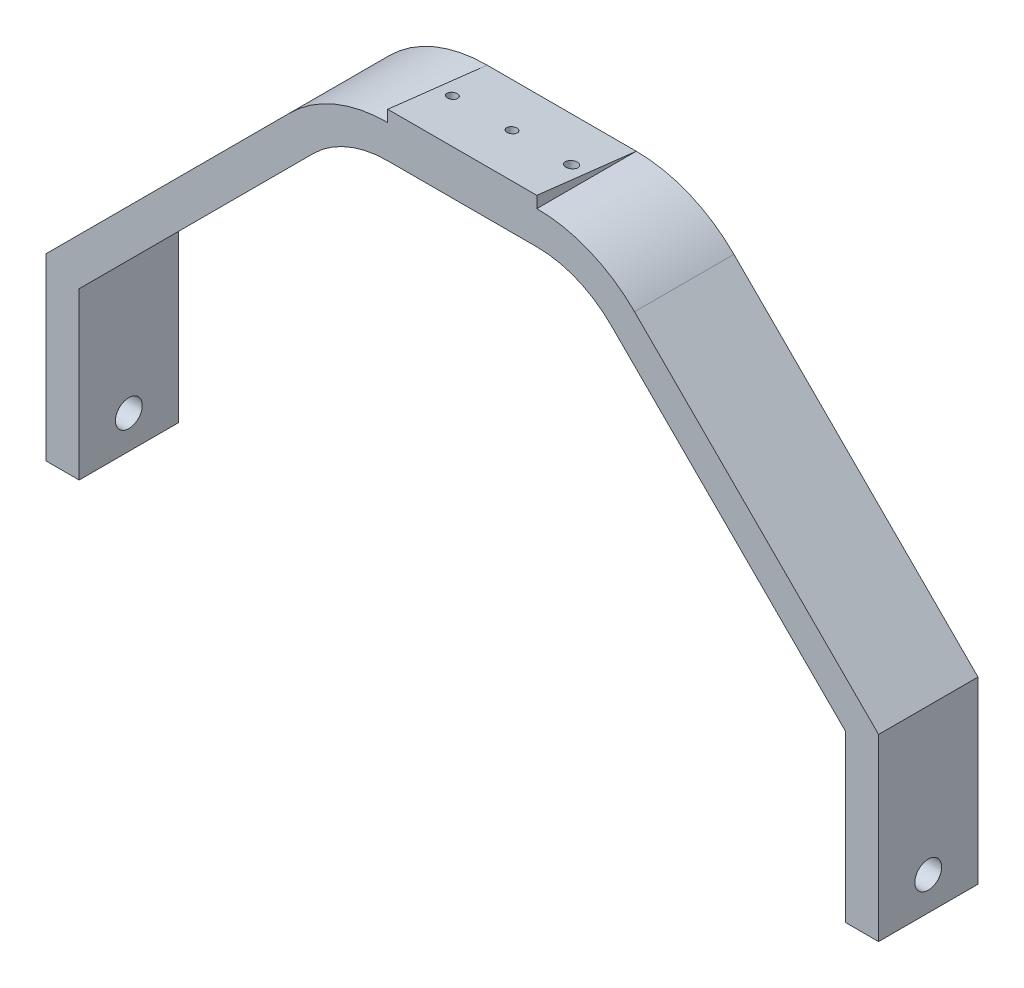
SolidWorks part; units mm, degrees
ref_plane "Alzado" through (0, 0, 0) normal (0, 0, 1) x (1, 0, 0)
ref_plane "Planta" through (0, 0, 0) normal (0, 1, 0) x (1, 0, 0)
ref_plane "Vista lateral" through (0, 0, 0) normal (1, 0, 0) x (0, 0, -1)
sketch "Croquis1" plane through (0, 0, 0) normal (0, 0, 1) x (1, 0, 0)
  line L0 (-22.5, -36.6894) -> (-68.1161, -36.6894) construction
  line L1 (-22.5, -5) -> (22.5, -5)
  line L3 (-22.5, 5) -> (22.5, 5)
  line L5 (0, -5) -> (0, 9.8205) construction
  line L6 (-51.9789, -7.2106) -> (-122.6896, -77.9212)
  line L7 (-68.1161, -36.6894) -> (22.5, -36.6894) construction
  line L8 (-22.5, -36.6894) -> (-55.2569, -3.9326) construction
  line L9 (-44.9078, -14.2816) -> (-115.6185, -84.9923)
  line L12 (-115.6185, -84.9923) -> (-115.6185, -134.9923)
  line L14 (22.5, -36.6894) -> (55.2569, -3.9326) construction
  line L15 (68.1161, -36.6894) -> (-22.5, -36.6894) construction
  line L16 (22.5, -36.6894) -> (68.1161, -36.6894) construction
  line L23 (-115.6185, -134.9923) -> (-125.6185, -134.9923)
  line L24 (-125.6185, -134.9923) -> (-125.6185, -80.8502)
  line L25 (-122.6896, -77.9212) -> (-125.6185, -80.8502)
  line L26 (44.9078, -14.2816) -> (115.6185, -84.9923)
  line L27 (51.9789, -7.2106) -> (122.6896, -77.9212)
  line L28 (122.6896, -77.9212) -> (125.6185, -80.8502)
  line L29 (125.6185, -134.9923) -> (125.6185, -80.8502)
  line L30 (115.6185, -134.9923) -> (125.6185, -134.9923)
  line L31 (115.6185, -84.9923) -> (115.6185, -134.9923)
  arc A0 (-22.5, -5) -> (-44.9078, -14.2816) centre (-22.5, -36.6894) ccw
  arc A1 (-22.5, 5) -> (-51.9789, -7.2106) centre (-22.5, -36.6894) ccw
  arc A2 (22.5, 5) -> (51.9789, -7.2106) centre (22.5, -36.6894) cw
  arc A3 (22.5, -5) -> (44.9078, -14.2816) centre (22.5, -36.6894) cw
  point P0 (0, 0)
extrude "Saliente-Extruir1" add sketch "Croquis1" along normal blind 30
sketch "Croquis3" plane through (-125.6185, 0, 0) normal (-1, 0, 0) x (0, 0, 1)
  line L0 (30, -134.9923) -> (0, -134.9923) construction
  circle A0 centre (15, -124.9923) radius 4.05
  dimension "D1" = 10
  dimension "D2" = 8.1
extrude "Cortar-Extruir1" cut sketch "Croquis3" against normal through all
sketch "Croquis4" plane through (0, 5, 0) normal (0, 1, 0) x (1, 0, 0)
  circle A1 centre (0, -15) radius 1.5
  circle A3 centre (18, -15) radius 1.5
  circle A4 centre (-18, -15) radius 1.5
  point P9 (0, -15)
extrude "Cortar-Extruir2" cut sketch "Croquis4" against normal through all
sketch "Croquis5" plane through (0, 5, 0) normal (0, 1, 0) x (1, 0, 0)
  line L1 (-22.5, 0) -> (22.5, 0)
  line L2 (-22.5, 0) -> (-22.5, -30)
  line L3 (-22.5, -30) -> (22.5, -30)
  line L4 (22.5, 0) -> (22.5, -30)
extrude "Saliente-Extruir2" add sketch "Croquis5" along normal blind 12
sketch "Croquis6" plane through (22.5, 0, 0) normal (1, 0, 0) x (0, 0, -1)
  line L0 (0, 5) -> (-30, 8.4711)
  line L1 (-30, 17) -> (-30, 5) construction
  line L4 (-30, 8.4711) -> (-30, 19.9231)
  line L5 (-30, 19.9231) -> (0, 19.9231)
  line L6 (0, 19.9231) -> (0, 5)
extrude "Cortar-Extruir3" cut sketch "Croquis6" against normal through all
sketch "Croquis7" plane through (0, -5, 0) normal (0, -1, 0) x (1, 0, 0)
sketch "Croquis8" plane through (0, -5, 0) normal (0, -1, 0) x (1, 0, 0)
  circle A0 centre (0, 15) radius 1.5
  circle A1 centre (-18, 15) radius 1.5
  circle A2 centre (18, 15) radius 1.5
extrude "Saliente-Extruir3" add sketch "Croquis8" against normal through all
sketch "Croquis9" plane through (0, 4.9339, -0.5709) normal (0, 0.9934, -0.1149) x (1, 0, 0)
  line L1 (-22.5, -0.5747) -> (22.5, -0.5747)
  line L2 (-22.5, -0.5747) -> (-22.5, -30.7748)
  line L3 (-22.5, -30.7748) -> (22.5, -30.7748)
  line L4 (22.5, -0.5747) -> (22.5, -30.7748)
extrude "Cortar-Extruir5" cut sketch "Croquis9" along normal blind 10
sketch "Croquis10" plane through (0, 4.9339, -0.5709) normal (0, 0.9934, -0.1149) x (1, 0, 0)
  circle A0 centre (0, -15.6748) radius 1.5
  circle A1 centre (-18, -15.6748) radius 1.5
  circle A2 centre (18, -15.6748) radius 1.735
  point P5 (0, -15.6748)
extrude "Cortar-Extruir6" cut sketch "Croquis10" against normal blind 18
sketch "Croquis11" plane through (-22.5, 0, 0) normal (-1, 0, 0) x (0, 0, 1)
  line L0 (30, 5) -> (30, 8.4711)
  line L1 (30, 8.4711) -> (0, 5)
  line L2 (0, 5) -> (30, 5)
  dimension "D1" = 30.2001
  dimension "D2" = 3.4711
  dimension "D3" = 30
